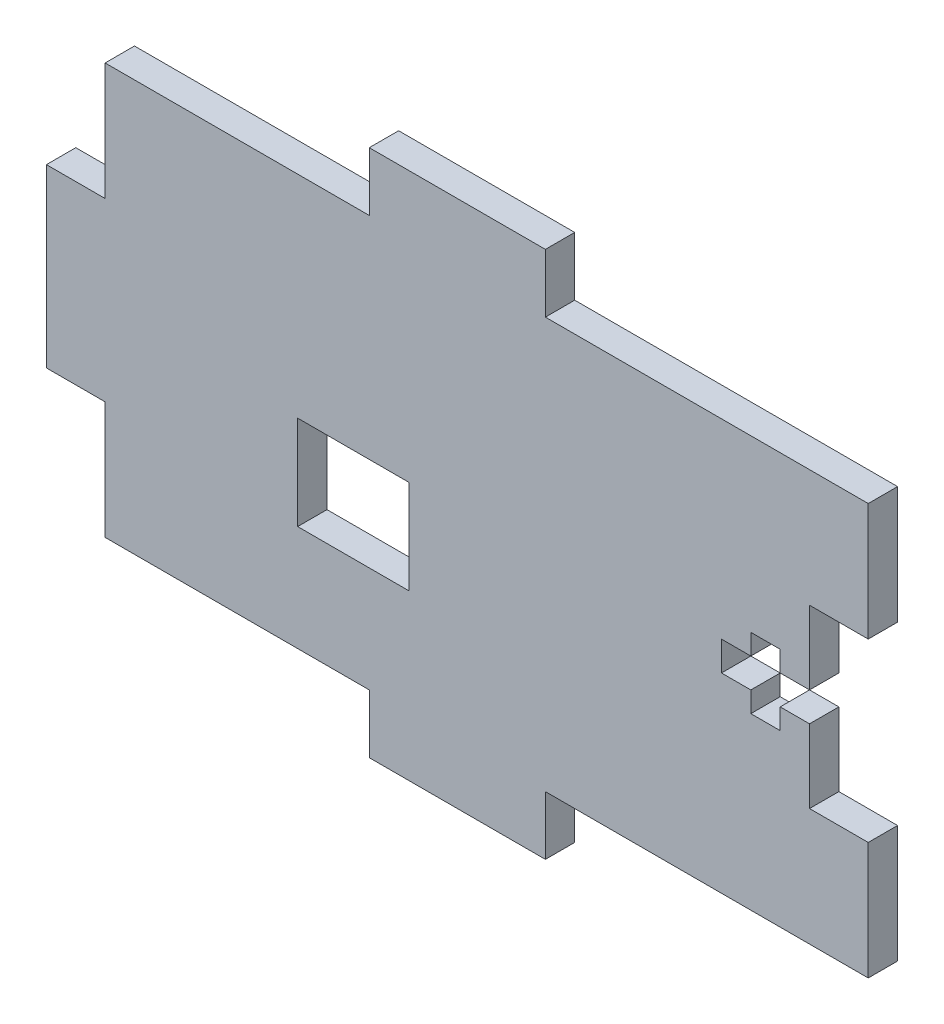
SolidWorks part; units mm, degrees
ref_plane "Front Plane" through (0, 0, 0) normal (0, 0, 1) x (1, 0, 0)
ref_plane "Top Plane" through (0, 0, 0) normal (0, 1, 0) x (1, 0, 0)
ref_plane "Right Plane" through (0, 0, 0) normal (1, 0, 0) x (0, 0, -1)
sketch "Sketch1" plane through (0, 0, 0) normal (0, 0, 1) x (1, 0, 0)
  line L1 (0, 0) -> (82.55, 0)
  line L2 (0, 0) -> (0, 44.45)
  line L3 (0, 44.45) -> (82.55, 44.45)
  line L4 (82.55, 0) -> (82.55, 44.45)
  dimension "D1" = 44.45
  dimension "D2" = 82.55
extrude "Boss-Extrude1" add sketch "Sketch1" along normal blind 3.175
sketch "Sketch2" plane through (0, 0, 3.175) normal (0, 0, 1) x (1, 0, 0)
  line L0 (0, -1.7463) -> (0, 1.7463) construction
  line L1 (0, 31.75) -> (-6.35, 31.75)
  line L2 (0, 31.75) -> (0, 12.7)
  line L3 (0, 12.7) -> (-6.35, 12.7)
  line L4 (-6.35, 31.75) -> (-6.35, 12.7)
  line L5 (82.55, 44.45) -> (0, 44.45) construction
  dimension "D1" = 6.35
  dimension "D2" = 19.05
  dimension "D3" = 12.7
extrude "Boss-Extrude2" add sketch "Sketch2" against normal blind 3.175
sketch "Sketch5" plane through (0, 0, 3.175) normal (0, 0, 1) x (1, 0, 0)
  line L0 (82.55, 44.45) -> (0, 44.45) construction
  line L1 (28.575, 44.45) -> (47.625, 44.45)
  line L2 (28.575, 44.45) -> (28.575, 50.8)
  line L3 (28.575, 50.8) -> (47.625, 50.8)
  line L4 (47.625, 44.45) -> (47.625, 50.8)
  line L6 (-6.35, 22.225) -> (82.55, 22.225) construction
  line L7 (47.625, 0) -> (47.625, -6.35)
  line L8 (28.575, -6.35) -> (47.625, -6.35)
  line L9 (28.575, 0) -> (28.575, -6.35)
  line L10 (28.575, 0) -> (47.625, 0)
  line L13 (-6.35, 31.75) -> (-6.35, 12.7) construction
  line L14 (82.55, 0) -> (82.55, 44.45) construction
  point P12 (38.1, 0)
  point P18 (38.1, 22.225)
  point P19 (38.1, 44.45)
  dimension "D1" = 19.05
  dimension "D2" = 6.35
extrude "Boss-Extrude3" add sketch "Sketch5" against normal blind 3.175
sketch "Sketch3" plane through (0, 0, 3.175) normal (0, 0, 1) x (1, 0, 0)
  line L0 (82.55, 0) -> (82.55, 44.45) construction
  line L1 (82.55, 12.7) -> (76.2, 12.7)
  line L2 (82.55, 12.7) -> (82.55, 31.75)
  line L3 (82.55, 31.75) -> (76.2, 31.75)
  line L4 (76.2, 12.7) -> (76.2, 31.75)
  line L5 (82.55, 44.45) -> (47.625, 44.45) construction
  dimension "D1" = 19.05
  dimension "D2" = 6.35
  dimension "D3" = 12.7
extrude "Cut-Extrude1" cut sketch "Sketch3" against normal blind 3.175
sketch "Sketch6" plane through (0, 0, 3.175) normal (0, 0, 1) x (1, 0, 0)
  line L0 (11.43, 16.51) -> (64.77, 16.51) construction
  line L1 (47.625, 50.8) -> (28.575, 50.8) construction
  line L3 (20.828, 11.43) -> (32.893, 11.43)
  line L4 (20.828, 11.43) -> (20.828, 21.59)
  line L5 (20.828, 21.59) -> (32.893, 21.59)
  line L6 (32.893, 11.43) -> (32.893, 21.59)
  line L7 (20.828, 11.43) -> (32.893, 21.59) construction
  line L8 (20.828, 21.59) -> (32.893, 11.43) construction
  line L9 (1.7463, 0) -> (-1.7463, 0) construction
  point P2 (26.8605, 16.51)
  point P3 (38.1, 16.51)
  point P4 (38.1, 50.8)
  point P5 (26.8605, 16.51)
  dimension "D1" = 53.34
  dimension "D2" = 15.4305
  dimension "D3" = 12.065
  dimension "D4" = 10.16
  dimension "D5" = 11.43
extrude "Cut-Extrude2" cut sketch "Sketch6" against normal through all
sketch "Sketch7" plane through (0, 0, 3.175) normal (0, 0, 1) x (1, 0, 0)
  line L0 (10.9273, 22.225) -> (30.8793, 22.225) construction
  line L1 (69.85, 26.035) -> (73.025, 26.035)
  line L2 (69.85, 26.035) -> (69.85, 23.8125)
  line L3 (69.85, 18.415) -> (73.025, 18.415)
  line L4 (73.025, 26.035) -> (73.025, 23.8125)
  line L5 (69.85, 26.035) -> (73.025, 18.415) construction
  line L6 (69.85, 18.415) -> (73.025, 26.035) construction
  line L7 (28.575, 44.45) -> (0, 44.45) construction
  line L8 (76.2, 31.75) -> (76.2, 12.7) construction
  line L9 (69.85, 20.6375) -> (69.85, 18.415)
  line L10 (76.2, 20.6375) -> (73.025, 20.6375)
  line L11 (76.2, 20.6375) -> (76.2, 23.8125)
  line L12 (76.2, 23.8125) -> (73.025, 23.8125)
  line L13 (66.675, 20.6375) -> (66.675, 23.8125)
  line L14 (76.2, 20.6375) -> (66.675, 23.8125) construction
  line L15 (76.2, 23.8125) -> (66.675, 20.6375) construction
  line L16 (69.85, 23.8125) -> (66.675, 23.8125)
  line L17 (69.85, 20.6375) -> (66.675, 20.6375)
  line L20 (73.025, 20.6375) -> (73.025, 18.415)
  point P0 (71.4375, 22.225)
  point P11 (71.4375, 22.225)
  dimension "D1" = 22.225
  dimension "D2" = 3.175
  dimension "D3" = 3.175
  dimension "D4" = 7.62
  dimension "D5" = 9.525
  dimension "D6" = 3.175
extrude "Cut-Extrude3" cut sketch "Sketch7" against normal through all
